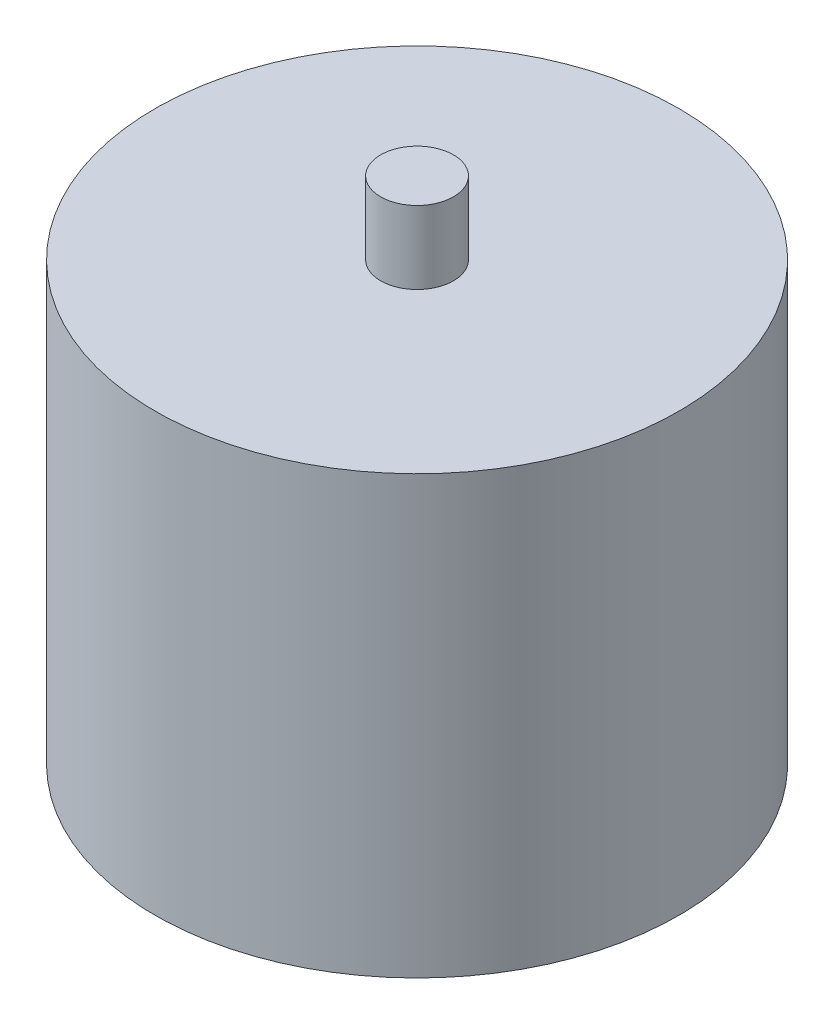
SolidWorks part; units mm, degrees
ref_plane "Front Plane" through (0, 0, 0) normal (0, 0, 1) x (1, 0, 0)
ref_plane "Top Plane" through (0, 0, 0) normal (0, 1, 0) x (1, 0, 0)
ref_plane "Right Plane" through (0, 0, 0) normal (1, 0, 0) x (0, 0, -1)
sketch "Sketch1" plane through (0, 0, 0) normal (0, 1, 0) x (1, 0, 0)
  circle A0 centre (0, 0) radius 11.43
  dimension "D1" = 22.86
extrude "Boss-Extrude1" add sketch "Sketch1" along normal blind 19.05
sketch "Sketch2" plane through (0, 19.05, 0) normal (0, 1, 0) x (1, 0, 0)
  circle A0 centre (0, 0) radius 1.5875
  dimension "D1" = 3.175
extrude "Boss-Extrude2" add sketch "Sketch2" along normal blind 3.175
sketch "Sketch3" plane through (0, 22.225, 0) normal (0, 1, 0) x (1, 0, 0)
  circle A0 centre (0, 0) radius 63.5
  dimension "D1" = 127
